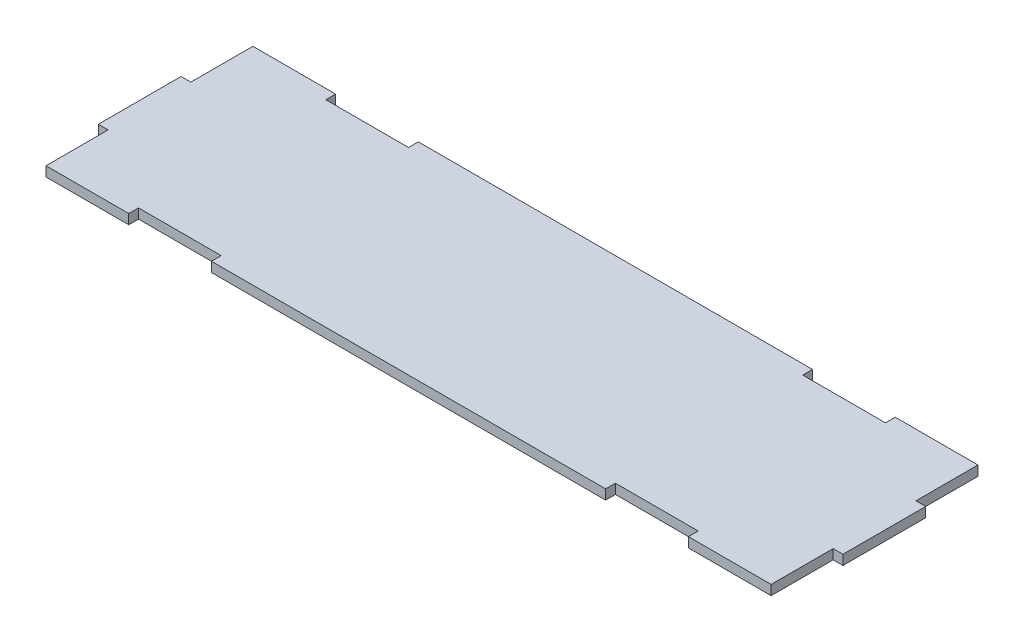
SolidWorks part; units mm, degrees
ref_plane "Front Plane" through (0, 0, 0) normal (0, 0, 1) x (1, 0, 0)
ref_plane "Top Plane" through (0, 0, 0) normal (0, 1, 0) x (1, 0, 0)
ref_plane "Right Plane" through (0, 0, 0) normal (1, 0, 0) x (0, 0, -1)
sketch "Sketch1" plane through (0, 0, 0) normal (0, 1, 0) x (1, 0, 0)
  line L0 (-47.407, 79.0049) -> (-27.407, 79.0049)
  line L5 (-27.407, 79.0049) -> (-27.407, 76.6427)
  line L6 (-27.407, 76.6427) -> (-7.407, 76.6427)
  line L7 (-7.407, 76.6427) -> (-7.407, 79.0049)
  line L8 (-7.407, 79.0049) -> (87.8686, 79.0049)
  line L9 (87.8686, 79.0049) -> (87.8686, 76.6427)
  line L10 (87.8686, 76.6427) -> (107.8686, 76.6427)
  line L11 (107.8686, 76.6427) -> (107.8686, 79.0049)
  line L12 (107.8686, 79.0049) -> (127.8686, 79.0049)
  line L13 (-47.407, 79.0049) -> (-47.407, 64.0049)
  line L14 (-47.407, 64.0049) -> (-49.7692, 64.0049)
  line L15 (-49.7692, 64.0049) -> (-49.7692, 44.0049)
  line L16 (-49.7692, 44.0049) -> (-47.407, 44.0049)
  line L17 (-47.407, 44.0049) -> (-47.407, 29.0049)
  line L18 (127.8686, 79.0049) -> (127.8686, 64.0049)
  line L19 (127.8686, 64.0049) -> (130.2308, 64.0049)
  line L20 (130.2308, 64.0049) -> (130.2308, 44.0049)
  line L21 (130.2308, 44.0049) -> (127.8686, 44.0049)
  line L22 (127.8686, 44.0049) -> (127.8686, 29.0049)
  line L23 (-47.407, 29.0049) -> (-27.407, 29.0049)
  line L24 (-27.407, 29.0049) -> (-27.407, 31.3671)
  line L25 (-27.407, 31.3671) -> (-7.407, 31.3671)
  line L26 (-7.407, 31.3671) -> (-7.407, 29.0049)
  line L27 (-7.407, 29.0049) -> (87.8686, 29.0049)
  line L28 (87.8686, 29.0049) -> (87.8686, 31.3671)
  line L29 (87.8686, 31.3671) -> (107.8686, 31.3671)
  line L30 (107.8686, 31.3671) -> (107.8686, 29.0049)
  line L31 (107.8686, 29.0049) -> (127.8686, 29.0049)
  dimension "D2" = 50
  dimension "D3" = 20
  dimension "D4" = 20
  dimension "D5" = 20
  dimension "D6" = 20
  dimension "D7" = 2.3622
  dimension "D8" = 2.3622
  dimension "D9" = 2.3622
  dimension "D10" = 2.3622
  dimension "D11" = 180
  dimension "D12" = 2.3622
  dimension "D13" = 2.3622
  dimension "D14" = 15
  dimension "D15" = 20
  dimension "D16" = 20
  dimension "D17" = 15
  dimension "D18" = 2.3622
  dimension "D19" = 2.3622
  dimension "D20" = 20
  dimension "D21" = 20
  dimension "D22" = 20
  dimension "D23" = 20
  dimension "D24" = 2.3622
  dimension "D25" = 2.3622
  dimension "D26" = 2.3622
extrude "Boss-Extrude1" add sketch "Sketch1" along normal blind 2.3622
